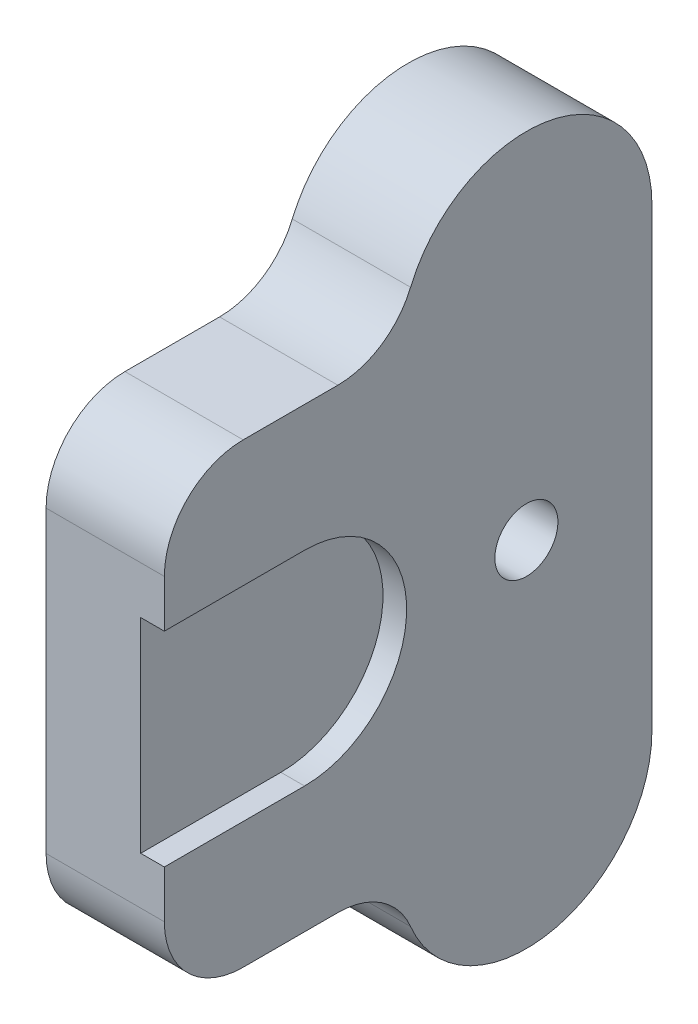
SolidWorks part; units mm, degrees
ref_plane "Front Plane" through (0, 0, 0) normal (1, 0, 0) x (0, 1, 0)
ref_plane "Top Plane" through (0, 0, 0) normal (0, 0, 1) x (0, 1, 0)
ref_plane "Right Plane" through (0, 0, 0) normal (0, 1, 0) x (-1, 0, 0)
sketch "Sketch1" plane through (0, 0, 0) normal (1, 0, 0) x (0, 1, 0)
  line L0 (-28.9545, 0) -> (33.8464, 0) construction
  line L3 (-28.9686, 19.054) -> (-28.9686, -12.7893) construction
  line L4 (0, 49.054) -> (0, -56.7378) construction
  line L6 (-28.9686, -12.7893) -> (28.9686, -12.7893)
  line L7 (44.5791, 0) -> (-44.5791, 0) construction
  line L9 (18.9686, 49.054) -> (-18.9686, 49.054)
  line L12 (-28.9686, 39.054) -> (-28.9686, 27.0474)
  line L13 (28.9686, 19.054) -> (28.9686, -12.7893) construction
  line L14 (28.9686, 39.054) -> (28.9686, 27.0474)
  line L15 (-28.9686, 19.054) -> (28.9686, 19.054) construction
  line L16 (-28.9686, 19.054) -> (28.9686, 19.054) construction
  arc A3 (-35.1108, 17.8215) -> (-28.9686, -12.7893) centre (-28.9686, 3.1323) ccw
  arc A4 (-18.9686, 49.054) -> (-28.9686, 39.054) centre (-18.9686, 39.054) ccw
  arc A5 (-35.1108, 17.8215) -> (-28.9686, 27.0474) centre (-38.9686, 27.0474) ccw
  arc A6 (35.1108, 17.8215) -> (28.9686, 27.0474) centre (38.9686, 27.0474) cw
  arc A7 (18.9686, 49.054) -> (28.9686, 39.054) centre (18.9686, 39.054) cw
  arc A8 (35.1108, 17.8215) -> (28.9686, -12.7893) centre (28.9686, 3.1323) cw
  point P20 (0, 0)
  dimension "D1" = 10
  dimension "D2" = 10
extrude "Boss-Extrude3" add sketch "Sketch1" along normal blind 15
sketch "Sketch3" plane through (15, 0, 0) normal (1, 0, 0) x (0, 1, 0)
  line L0 (-44.8903, 3.1323) -> (44.8903, 3.1323) construction
  line L2 (-28.9686, -12.7893) -> (28.9686, -12.7893) construction
  line L3 (0, -12.7893) -> (0, 49.054) construction
  line L4 (18.9686, 49.054) -> (-18.9686, 49.054) construction
  arc A3 (-35.1108, 17.8215) -> (-28.9686, -12.7893) centre (-28.9686, 3.1323) ccw construction
  arc A4 (28.9686, -12.7893) -> (35.1108, 17.8215) centre (28.9686, 3.1323) ccw construction
  circle A5 centre (0, 3.1323) radius 4
extrude "Cut-Extrude3" cut sketch "Sketch3" against normal blind 14.0462
sketch "Sketch4" plane through (15, 0, 0) normal (1, 0, 0) x (0, 1, 0)
  line L0 (-12.95, 49.054) -> (-12.95, 31.2677)
  line L4 (18.9686, 49.054) -> (-18.9686, 49.054) construction
  line L6 (0, 7.1323) -> (0, 31.2677) construction
  line L7 (12.95, 31.2677) -> (12.95, 49.054)
  line L8 (-12.95, 49.054) -> (12.95, 49.054)
  circle A1 centre (0, 3.1323) radius 4 construction
  circle A2 centre (0, 31.2677) radius 12.95 construction
  arc A3 (-12.95, 31.2677) -> (12.95, 31.2677) centre (0, 31.2677) ccw
extrude "Cut-Extrude4" cut sketch "Sketch4" against normal blind 3
